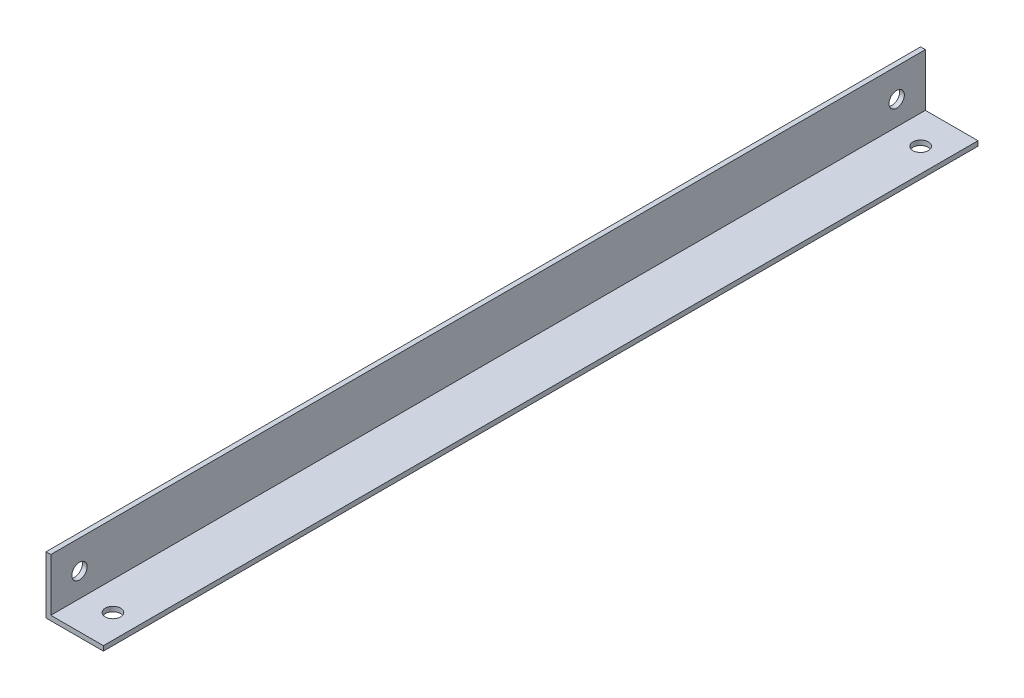
SolidWorks part; units mm, degrees
ref_plane "Front Plane" through (0, 0, 0) normal (0, 0, 1) x (1, 0, 0)
ref_plane "Top Plane" through (0, 0, 0) normal (0, 1, 0) x (1, 0, 0)
ref_plane "Right Plane" through (0, 0, 0) normal (1, 0, 0) x (0, 0, -1)
sketch "Sketch1" plane through (0, 0, 0) normal (0, 0, 1) x (1, 0, 0)
  line L0 (0, 0) -> (0, 30)
  line L1 (0, 30) -> (2.5, 30)
  line L2 (2.5, 30) -> (2.5, 2.5)
  line L3 (2.5, 2.5) -> (30, 2.5)
  line L4 (30, 2.5) -> (30, 0)
  line L5 (30, 0) -> (0, 0)
  dimension "D1" = 2.5
  dimension "D2" = 2.5
  dimension "D3" = 30
  dimension "D4" = 30
extrude "Boss-Extrude1" add sketch "Sketch1" along normal blind 457.2
sketch "Sketch2" plane through (0, 2.5, 0) normal (0, 1, 0) x (1, 0, 0)
  line L0 (-142.3856, -228.6) -> (299.1222, -228.6) construction
  line L1 (30, 0) -> (2.5, 0) construction
  line L2 (30, -457.2) -> (30, 0) construction
  line L3 (0, 0) -> (30, 0) construction
  circle A0 centre (17.5, -17.5) radius 4
  circle A1 centre (17.5, -439.7) radius 4
  point P2 (16.25, 0)
  point P9 (15, 0)
  dimension "D2" = 8
  dimension "D1" = 228.6
  dimension "D3" = 12.5
  dimension "D4" = 17.5
  dimension "D5" = 211.1
extrude "Cut-Extrude1" cut sketch "Sketch2" against normal through all
sketch "Sketch3" plane through (2.5, 0, 0) normal (1, 0, 0) x (0, 0, -1)
  line L0 (-228.6, 87.168) -> (-228.6, -67.2996) construction
  line L1 (0, 2.5) -> (0, 30) construction
  line L4 (-457.2, 30) -> (0, 30) construction
  circle A0 centre (-15, 15) radius 4
  circle A1 centre (-442.2, 15) radius 4
  point P6 (0, 16.25)
  dimension "D2" = 8
  dimension "D5" = 8
  dimension "D1" = 228.6
  dimension "D3" = 15
  dimension "D4" = 15
  dimension "D6" = 15
extrude "Cut-Extrude2" cut sketch "Sketch3" against normal through all
